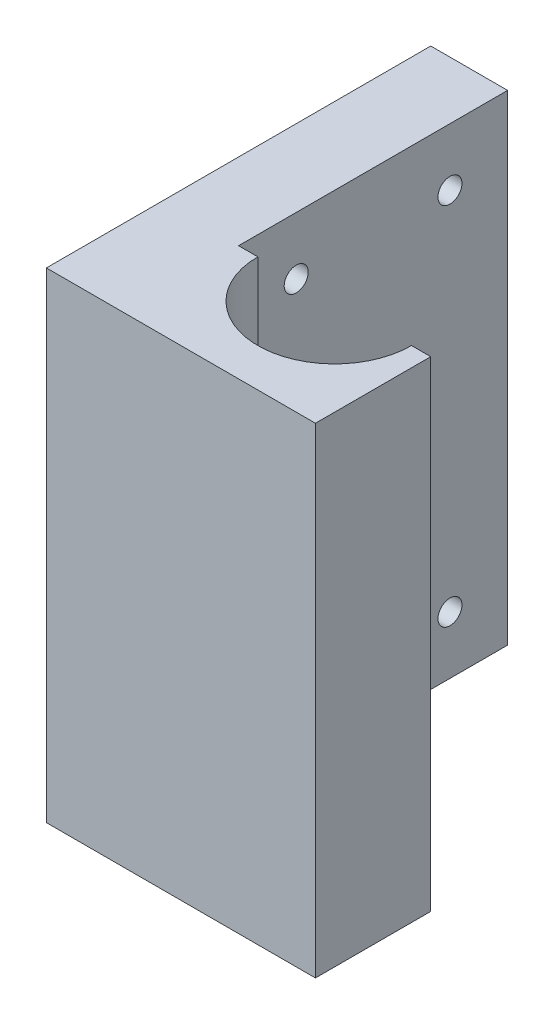
SolidWorks part; units mm, degrees
ref_plane "前视基准面" through (0, 0, 0) normal (0, 0, 1) x (1, 0, 0)
ref_plane "上视基准面" through (0, 0, 0) normal (0, 1, 0) x (1, 0, 0)
ref_plane "右视基准面" through (0, 0, 0) normal (1, 0, 0) x (0, 0, -1)
sketch "草图1" plane through (0, 0, 0) normal (0, 1, 0) x (1, 0, 0)
  line L0 (0, 0) -> (0, 28)
  line L1 (0, 28) -> (-8, 28)
  line L2 (-8, 28) -> (-8, -12)
  line L3 (-8, -12) -> (20, -12)
  line L4 (20, -12) -> (20, 0)
  line L5 (20, 0) -> (18, 0)
  line L6 (2, 0) -> (0, 0)
  arc A0 (2, 0) -> (18, 0) centre (10, 0) ccw
  dimension "D1" = 16
  dimension "D2" = 28
  dimension "D3" = 20
  dimension "D4" = 12
  dimension "D5" = 40
extrude "凸台-拉伸1" add sketch "草图1" along normal blind 50
hole_wizard "M3 螺纹孔1" positions "草图2" profile "草图3" tap size "M3" standard "GB" end condition through all
sketch "草图2" plane through (0, 0, 0) normal (1, 0, 0) x (0, 0, -1)
  line L0 (28, 50) -> (28, 0) construction
  line L1 (0, 50) -> (0, 0) construction
  line L2 (0, 50) -> (28, 50) construction
  line L3 (0, 0) -> (28, 0) construction
  point P0 (22, 44)
  point P2 (6, 44)
  point P4 (6, 6)
  point P6 (22, 6)
  dimension "D1" = 6
  dimension "D2" = 6
  dimension "D3" = 6
  dimension "D4" = 6
  dimension "D5" = 6
  dimension "D6" = 6
  dimension "D7" = 6
  dimension "D8" = 6
sketch "草图3" plane through (0, 44, -22) normal (0, 1, 0) x (0, 0, -1)
  line L0 (0, 0) -> (0, 8)
  line L1 (0, 8) -> (1.25, 8)
  line L2 (1.25, 8) -> (1.25, 0)
  line L5 (1.25, 0) -> (0, 0)
  line L11 (0, -6.35) -> (0, 107.95) construction
  dimension "通孔螺纹孔钻头直径" = 2.5
  dimension "通孔螺纹孔钻头深度" = 8
cosmetic thread "孔螺蚊线1"
cosmetic thread "孔螺蚊线2"
cosmetic thread "孔螺蚊线3"
cosmetic thread "孔螺蚊线4"
